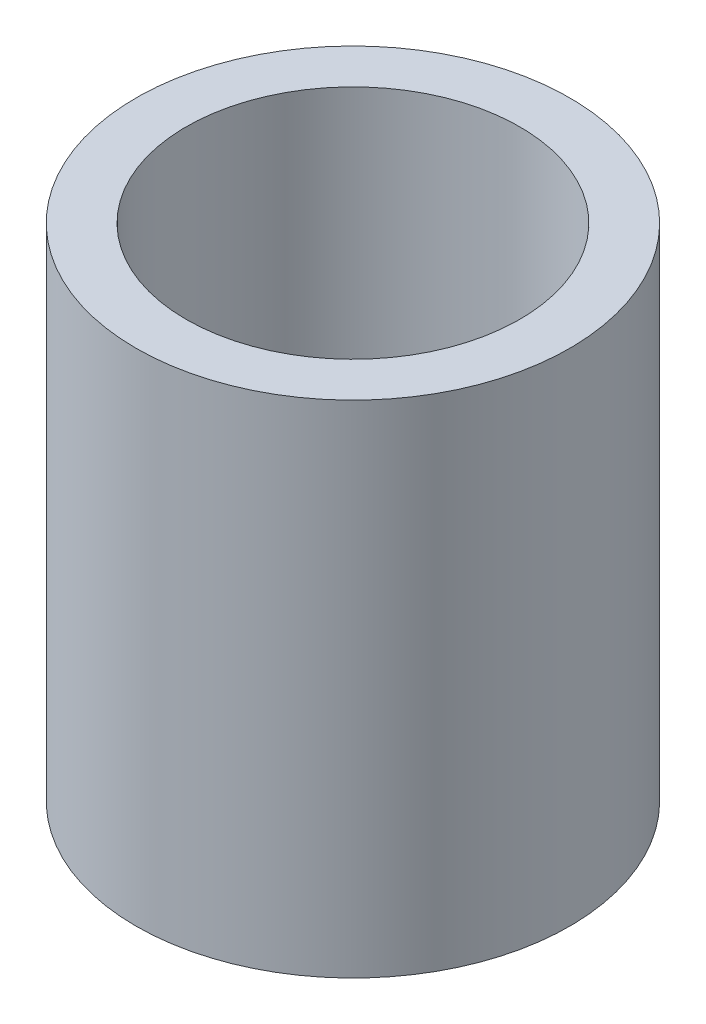
SolidWorks part; units mm, degrees
ref_plane "Front Plane" through (0, 0, 0) normal (0, 0, 1) x (1, 0, 0)
ref_plane "Top Plane" through (0, 0, 0) normal (0, 1, 0) x (1, 0, 0)
ref_plane "Right Plane" through (0, 0, 0) normal (1, 0, 0) x (0, 0, -1)
sketch "Sketch1" plane through (0, 0, 0) normal (0, 1, 0) x (1, 0, 0)
  circle A0 centre (0, 0) radius 10
  circle A1 centre (0, 0) radius 13
  dimension "D2" = 20
  dimension "D1" = 3
extrude "Boss-Extrude1" add sketch "Sketch1" along normal blind 30
